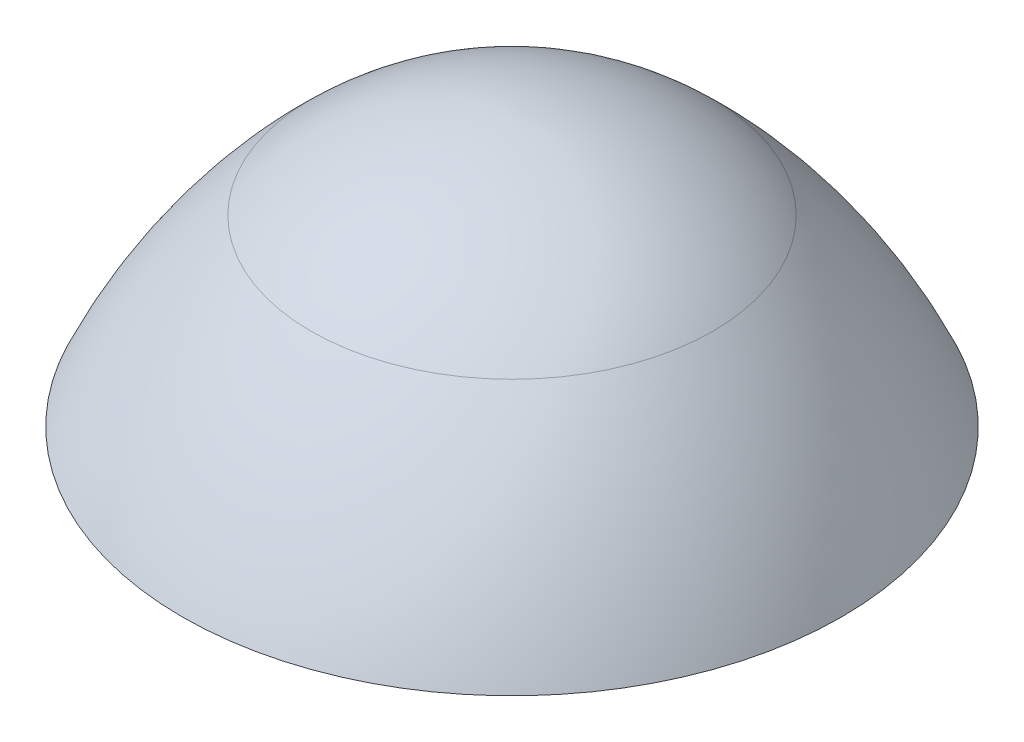
SolidWorks part; units mm, degrees
ref_plane "Front Plane" through (0, 0, 0) normal (0, 0, 1) x (1, 0, 0)
ref_plane "Top Plane" through (0, 0, 0) normal (0, 1, 0) x (1, 0, 0)
ref_plane "Right Plane" through (0, 0, 0) normal (1, 0, 0) x (0, 0, -1)
sketch "Sketch4" plane through (0, 0, 0) normal (1, 0, 0) x (0, 0, -1)
  line L0 (0, 0) -> (-4.93, 0)
  line L1 (0, 0) -> (0, 4)
  arc A0 (-4.93, 0) -> (-3.0051, 2.7373) centre (3.0592, -3.5725) cw
  arc A1 (-3.0051, 2.7373) -> (0, 4) centre (0.1359, -0.5309) cw
  dimension "D2" = 4
  dimension "D1" = 4.93
revolve "Revolve1" add sketch "Sketch4" angle 360 about L1
shell "Shell1" thickness 2
